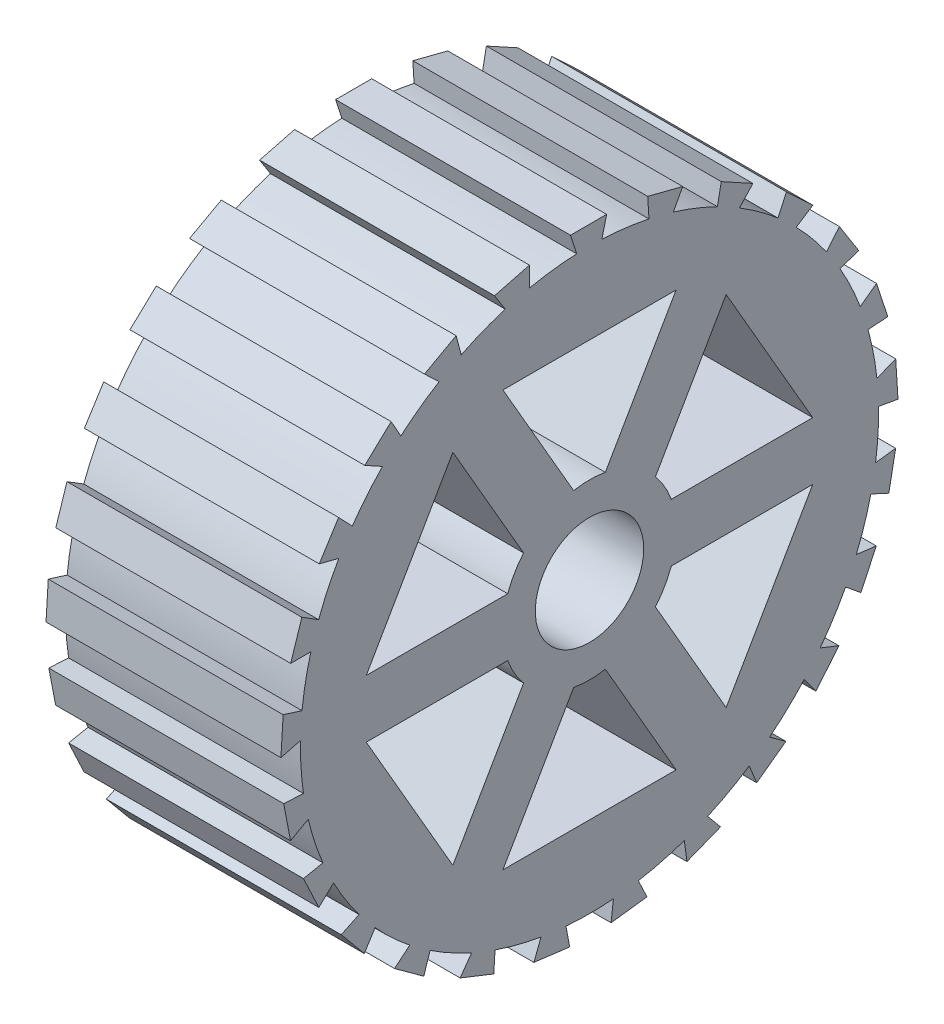
SolidWorks part; units mm, degrees
ref_plane "Front Plane" through (0, 0, 0) normal (0, 0, 1) x (1, 0, 0)
ref_plane "Top Plane" through (0, 0, 0) normal (0, 1, 0) x (1, 0, 0)
ref_plane "Right Plane" through (0, 0, 0) normal (1, 0, 0) x (0, 0, -1)
sketch "Sketch1" plane through (0, 0, 0) normal (1, 0, 0) x (0, 0, -1)
  circle A0 centre (0, 0) radius 80
  circle A1 centre (0, 0) radius 15
  dimension "D1" = 160
extrude "Boss-Extrude1" add sketch "Sketch1" along normal blind 65
sketch "Sketch2" plane through (65, 0, 0) normal (1, 0, 0) x (0, 0, -1)
  line L37 (-33.1976, -57.5) -> (33.1976, -57.5)
  line L38 (33.1976, -57.5) -> (66.3953, 0)
  line L39 (66.3953, 0) -> (33.1976, 57.5)
  line L40 (33.1976, 57.5) -> (-33.1976, 57.5)
  line L41 (-33.1976, 57.5) -> (-66.3953, 0)
  line L42 (-66.3953, 0) -> (-33.1976, -57.5)
  line L62 (-22.6274, -8) -> (-61.7765, -8)
  line L64 (-18.2419, -15.5959) -> (-37.8164, -49.5)
  line L68 (-18.2419, 15.5959) -> (-37.8164, 49.5)
  line L70 (-22.6274, 8) -> (-61.7765, 8)
  line L74 (4.3855, 23.5959) -> (23.96, 57.5)
  line L76 (-4.3855, 23.5959) -> (-23.96, 57.5)
  line L80 (22.6274, 8) -> (61.7765, 8)
  line L82 (18.2419, 15.5959) -> (37.8164, 49.5)
  line L86 (18.2419, -15.5959) -> (37.8164, -49.5)
  line L88 (22.6274, -8) -> (61.7765, -8)
  line L92 (-4.3855, -23.5959) -> (-23.96, -57.5)
  line L94 (4.3855, -23.5959) -> (23.96, -57.5)
  circle A1 centre (0, 0) radius 16
  arc A2 (-4.3855, -23.5959) -> (4.3855, -23.5959) centre (0, 0) ccw
  arc A3 (-22.6274, -8) -> (-18.2419, -15.5959) centre (0, 0) ccw
  arc A4 (-18.2419, 15.5959) -> (-22.6274, 8) centre (0, 0) ccw
  arc A5 (4.3855, 23.5959) -> (-4.3855, 23.5959) centre (0, 0) ccw
  arc A6 (22.6274, 8) -> (18.2419, 15.5959) centre (0, 0) ccw
  arc A7 (18.2419, -15.5959) -> (22.6274, -8) centre (0, 0) ccw
  point P6 (12.0813, 20.8656)
  point P8 (0, 0)
  point P10 (12.0813, 20.8656)
  point P12 (0, 0)
  dimension "D3" = 32
extrude "Cut-Extrude1" cut sketch "Sketch2" against normal blind 65 contours A4 L68 L41 L70 | A3 L62 L42 L64 | A2 L92 L37 L94 | A7 L86 L38 L88 | A6 L80 L39 L82 | A5 L74 L40 L76
sketch "Sketch3" plane through (65, 0, 0) normal (1, 0, 0) x (0, 0, -1)
  line L0 (-5.2549, 85.2412) -> (4.7451, 85.2412)
  line L1 (-2.9886, 78.2412) -> (3.0114, 78.2412)
  line L2 (-2.9886, 78.2412) -> (-5.2549, 85.2412)
  line L3 (3.0114, 78.2412) -> (4.7451, 85.2412)
  line L4 (22.3746, 75.0342) -> (25.7946, 81.3831)
  line L5 (16.1088, 83.87) -> (25.7946, 81.3831)
  line L6 (16.5631, 76.5263) -> (16.1088, 83.87)
  line L7 (16.5631, 76.5263) -> (22.3746, 75.0342)
  line L8 (40.3319, 67.1125) -> (45.2234, 72.4115)
  line L9 (36.4603, 77.229) -> (45.2234, 72.4115)
  line L10 (35.0741, 70.003) -> (36.4603, 77.229)
  line L11 (35.0741, 70.003) -> (40.3319, 67.1125)
  line L12 (55.755, 54.9739) -> (61.8106, 58.8899)
  line L13 (54.5209, 65.7354) -> (61.8106, 58.8899)
  line L14 (51.3812, 59.0812) -> (54.5209, 65.7354)
  line L15 (51.3812, 59.0812) -> (55.755, 54.9739)
  line L16 (67.6748, 39.3811) -> (74.5141, 41.6681)
  line L17 (69.1558, 50.1114) -> (74.5141, 41.6681)
  line L18 (64.4599, 44.447) -> (69.1558, 50.1114)
  line L19 (64.4599, 44.447) -> (67.6748, 39.3811)
  line L20 (75.3424, 21.3138) -> (82.5355, 21.8282)
  line L21 (79.4453, 31.3387) -> (82.5355, 21.8282)
  line L22 (73.4883, 27.0201) -> (79.4453, 31.3387)
  line L23 (73.4883, 27.0201) -> (75.3424, 21.3138)
  line L24 (78.2759, 1.9073) -> (85.3709, 0.6166)
  line L25 (84.743, 10.5969) -> (85.3709, 0.6166)
  line L26 (77.8991, 7.8955) -> (84.743, 10.5969)
  line L27 (77.8991, 7.8955) -> (78.2759, 1.9073)
  line L28 (76.291, -17.619) -> (82.8422, -20.6336)
  line L29 (84.716, -10.8108) -> (82.8422, -20.6336)
  line L30 (77.4153, -11.7253) -> (84.716, -10.8108)
  line L31 (77.4153, -11.7253) -> (76.291, -17.619)
  line L32 (69.5125, -36.0383) -> (75.1082, -40.5874)
  line L33 (79.366, -31.5391) -> (75.1082, -40.5874)
  line L34 (72.0672, -30.6094) -> (79.366, -31.5391)
  line L35 (72.0672, -30.6094) -> (69.5125, -36.0383)
  line L36 (58.3663, -52.1932) -> (62.6549, -57.9909)
  line L37 (69.0291, -50.2858) -> (62.6549, -57.9909)
  line L38 (62.1909, -47.5701) -> (69.0291, -50.2858)
  line L39 (62.1909, -47.5701) -> (58.3663, -52.1932)
  line L40 (43.5527, -65.0685) -> (46.2647, -71.7507)
  line L41 (54.3548, -65.8728) -> (46.2647, -71.7507)
  line L42 (48.4068, -61.5418) -> (54.3548, -65.8728)
  line L43 (48.4068, -61.5418) -> (43.5527, -65.0685)
  line L44 (26.0025, -73.8554) -> (26.9675, -81.002)
  line L45 (36.2653, -77.3208) -> (26.9675, -81.002)
  line L46 (31.5812, -71.6467) -> (36.2653, -77.3208)
  line L47 (31.5812, -71.6467) -> (26.0025, -73.8554)
  line L48 (6.8185, -78.0017) -> (5.9759, -85.1638)
  line L49 (15.8971, -83.9104) -> (5.9759, -85.1638)
  line L50 (12.7712, -77.2497) -> (15.8971, -83.9104)
  line L51 (12.7712, -77.2497) -> (6.8185, -78.0017)
  line L52 (-12.7939, -77.2468) -> (-15.3912, -83.9743)
  line L53 (-5.4701, -85.2277) -> (-15.3912, -83.9743)
  line L54 (-6.8412, -77.9988) -> (-5.4701, -85.2277)
  line L55 (-6.8412, -77.9988) -> (-12.7939, -77.2468)
  line L56 (-31.6025, -71.6382) -> (-35.7912, -77.5085)
  line L57 (-26.4935, -81.1897) -> (-35.7912, -77.5085)
  line L58 (-26.0238, -73.847) -> (-26.4935, -81.1897)
  line L59 (-26.0238, -73.847) -> (-31.6025, -71.6382)
  line L60 (-48.4253, -61.5284) -> (-53.9424, -66.1725)
  line L61 (-45.8522, -72.0503) -> (-53.9424, -66.1725)
  line L62 (-43.5712, -65.0551) -> (-45.8522, -72.0503)
  line L63 (-43.5712, -65.0551) -> (-48.4253, -61.5284)
  line L64 (-62.2054, -47.5525) -> (-68.7041, -50.6786)
  line L65 (-62.3298, -58.3838) -> (-68.7041, -50.6786)
  line L66 (-58.3809, -52.1755) -> (-62.3298, -58.3838)
  line L67 (-58.3809, -52.1755) -> (-62.2054, -47.5525)
  line L68 (-72.077, -30.5886) -> (-79.1489, -32.0005)
  line L69 (-74.8911, -41.0487) -> (-79.1489, -32.0005)
  line L70 (-69.5223, -36.0176) -> (-74.8911, -41.0487)
  line L71 (-69.5223, -36.0176) -> (-72.077, -30.5886)
  line L72 (-77.4196, -11.7028) -> (-84.6205, -11.3116)
  line L73 (-82.7467, -21.1345) -> (-84.6205, -11.3116)
  line L74 (-76.2953, -17.5966) -> (-82.7467, -21.1345)
  line L75 (-76.2953, -17.5966) -> (-77.4196, -11.7028)
  line L76 (-77.8977, 7.9183) -> (-84.775, 10.088)
  line L77 (-85.4029, 0.1078) -> (-84.775, 10.088)
  line L78 (-78.2745, 1.9301) -> (-85.4029, 0.1078)
  line L79 (-78.2745, 1.9301) -> (-77.8977, 7.9183)
  line L80 (-73.4812, 27.0419) -> (-79.6029, 30.8538)
  line L81 (-82.6931, 21.3432) -> (-79.6029, 30.8538)
  line L82 (-75.3353, 21.3356) -> (-82.6931, 21.3432)
  line L83 (-75.3353, 21.3356) -> (-73.4812, 27.0419)
  line L84 (-64.4476, 44.4664) -> (-69.429, 49.6809)
  line L85 (-74.7873, 41.2376) -> (-69.429, 49.6809)
  line L86 (-67.6626, 39.4004) -> (-74.7873, 41.2376)
  line L87 (-67.6626, 39.4004) -> (-64.4476, 44.4664)
  line L88 (-51.3645, 59.0969) -> (-54.8926, 65.3864)
  line L89 (-62.1823, 58.5409) -> (-54.8926, 65.3864)
  line L90 (-55.7383, 54.9896) -> (-62.1823, 58.5409)
  line L91 (-55.7383, 54.9896) -> (-51.3645, 59.0969)
  line L92 (-35.054, 70.0141) -> (-36.9071, 76.9834)
  line L93 (-45.6702, 72.1658) -> (-36.9071, 76.9834)
  line L94 (-40.3119, 67.1235) -> (-45.6702, 72.1658)
  line L95 (-40.3119, 67.1235) -> (-35.054, 70.0141)
  line L96 (-16.541, 76.532) -> (-16.6026, 83.7432)
  line L97 (-26.2885, 81.2563) -> (-16.6026, 83.7432)
  line L98 (-22.3525, 75.0399) -> (-26.2885, 81.2563)
  line L99 (-22.3525, 75.0399) -> (-16.541, 76.532)
  point P3 (-0.2549, 85.2412)
  point P6 (0.0114, 78.2412)
  point P104 (0, 0)
  dimension "D1" = 10
  dimension "D2" = 6
  dimension "D3" = 103.91
  dimension "D5" = 7
  dimension "D4" = 25
extrude "Boss-Extrude2" add sketch "Sketch3" against normal blind 65
